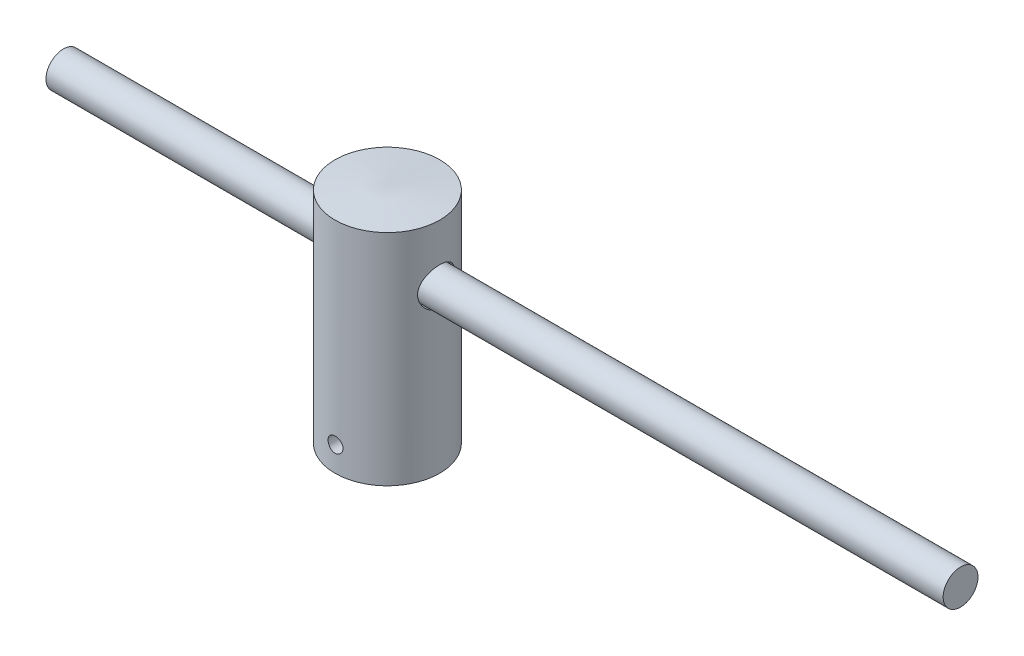
SolidWorks part; units mm, degrees
ref_plane "Front Plane" through (0, 0, 0) normal (0, 0, 1) x (1, 0, 0)
ref_plane "Top Plane" through (0, 0, 0) normal (0, 1, 0) x (1, 0, 0)
ref_plane "Right Plane" through (0, 0, 0) normal (1, 0, 0) x (0, 0, -1)
sketch "Sketch1" plane through (0, 0, 0) normal (0, 0, 1) x (1, 0, 0)
  line L0 (0, 19.2494) -> (0, -27.8445) construction
  line L1 (-6, 0) -> (-21, 0)
  line L2 (-21, 0) -> (-21, 88)
  line L3 (-21, 88) -> (0, 90)
  line L4 (0, 90) -> (0, 35)
  line L5 (-6, 0) -> (-6, 35)
  line L6 (-6, 35) -> (0, 35)
  dimension "D1" = 2
  dimension "D2" = 21
  dimension "D3" = 6
  dimension "D4" = 35
  dimension "D5" = 90
revolve "Revolve1" add sketch "Sketch1" angle 360 about L0
sketch "Sketch3" plane through (0, 0, 0) normal (1, 0, 0) x (0, 0, -1)
  line L0 (-21, 0) -> (21, 0) construction
  circle A0 centre (0, 65) radius 7.5
  dimension "D1" = 15
  dimension "D2" = 65
extrude "Cut-Extrude2" cut sketch "Sketch3" against normal through all and the other way through all
sketch "Sketch5" plane through (0, 0, 0) normal (1, 0, 0) x (0, 0, -1)
  circle A0 centre (0, 65) radius 6.9921
extrude "Boss-Extrude1" add sketch "Sketch5" along normal blind 230 and the other way blind 130 separate body
sketch "Sketch7" plane through (0, 0, 0) normal (0, 0, 1) x (1, 0, 0)
  circle A0 centre (0, 10) radius 3
  dimension "D1" = 6
  dimension "D2" = 10
extrude "Cut-Extrude3" cut sketch "Sketch7" along normal through all
